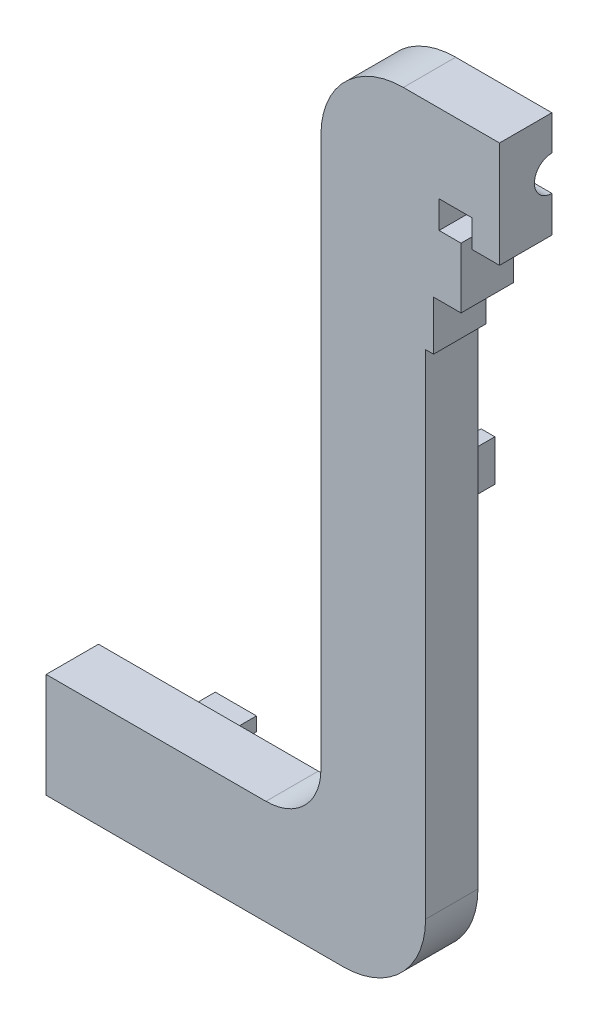
SolidWorks part; units mm, degrees
material "ABS"
ref_plane "Front Plane" through (0, 0, 0) normal (0, 0, 1) x (1, 0, 0)
ref_plane "Top Plane" through (0, 0, 0) normal (0, 1, 0) x (1, 0, 0)
ref_plane "Right Plane" through (0, 0, 0) normal (1, 0, 0) x (0, 0, -1)
sketch "Sketch1" plane through (0, 0, 0) normal (0, 0, 1) x (1, 0, 0)
  line L0 (-100, 0) -> (0, 0)
  line L1 (0, 0) -> (0, 250)
  line L2 (0, 250) -> (65, 250)
  line L3 (65, 250) -> (65, 211.9)
  line L4 (-100, -38.1) -> (38.1, -38.1)
  line L5 (38.1, -38.1) -> (38.1, 211.9)
  line L6 (38.1, 211.9) -> (65, 211.9)
  line L7 (-100, 0) -> (-100, -38.1)
  dimension "D1" = 100
  dimension "D2" = 250
  dimension "D3" = 65
  dimension "D4" = 38.1
extrude "Boss-Extrude1" add sketch "Sketch1" along normal blind 19.05
sketch "Sketch2" plane through (0, 0, 0) normal (0, 0, -1) x (-1, 0, 0)
  line L0 (-65, 230.95) -> (-39.05, 230.95)
  line L1 (-65, 211.9) -> (-65, 250) construction
  line L2 (100, -19.05) -> (0.95, -19.05)
  line L3 (100, 0) -> (100, -38.1) construction
  line L5 (-19.05, 210.95) -> (-19.05, 0.95)
  line L7 (-38.1, -38.1) -> (-38.1, 211.9) construction
  arc A0 (0.95, -19.05) -> (-19.05, 0.95) centre (0.95, 0.95) cw
  arc A1 (-39.05, 230.95) -> (-19.05, 210.95) centre (-39.05, 210.95) cw
  dimension "D2" = 20
  dimension "D1" = 19.05
sweep "Cut-Sweep1" cut path "Sketch2" circular profile diameter 12.7 parameters "D3"=12.7
fillet "Fillet1" radius 30 2 edges at (38.1, -38.1, 9.525) (0, 250, 9.525)
fillet "Fillet2" radius 20 1 edges at (0, 0, 9.525)
sketch "Sketch10" plane through (0, 0, 0) normal (0, 0, -1) x (-1, 0, 0)
  line L0 (0, 120) -> (-12.7, 120) construction
  line L17 (-19.05, 0.95) -> (-19.05, 210.95) construction
  line L18 (-12.7, 0.95) -> (-25.4, 0.95) construction
  line L23 (-12.7, 210.95) -> (-25.4, 210.95) construction
  line L24 (0, 220) -> (0, 20) construction
  line L29 (100, -19.05) -> (0.95, -19.05) construction
  line L30 (100, -25.4) -> (100, -12.7) construction
  line L35 (0.95, -12.7) -> (0.95, -25.4) construction
  line L36 (60, 0) -> (60, -12.7) construction
  line L47 (-3.85, 127.5) -> (-8.85, 127.5)
  line L48 (-3.85, 127.5) -> (-3.85, 112.5)
  line L49 (-3.85, 112.5) -> (-8.85, 112.5)
  line L50 (-8.85, 127.5) -> (-8.85, 112.5)
  line L51 (-3.85, 127.5) -> (-8.85, 112.5) construction
  line L52 (-3.85, 112.5) -> (-8.85, 127.5) construction
  line L53 (-12.7, 210.95) -> (-12.7, 0.95) construction
  line L54 (-34.25, 112.5) -> (-29.25, 127.5) construction
  line L55 (-34.25, 127.5) -> (-29.25, 112.5) construction
  line L56 (-38.1, 120) -> (-25.4, 120) construction
  line L57 (-29.25, 127.5) -> (-29.25, 112.5)
  line L58 (-34.25, 112.5) -> (-29.25, 112.5)
  line L59 (-34.25, 127.5) -> (-34.25, 112.5)
  line L60 (-34.25, 127.5) -> (-29.25, 127.5)
  line L61 (67.5, -3.85) -> (52.5, -3.85)
  line L62 (67.5, -3.85) -> (67.5, -8.85)
  line L63 (67.5, -8.85) -> (52.5, -8.85)
  line L64 (52.5, -3.85) -> (52.5, -8.85)
  line L65 (67.5, -3.85) -> (52.5, -8.85) construction
  line L66 (67.5, -8.85) -> (52.5, -3.85) construction
  line L67 (20, 0) -> (100, 0) construction
  line L68 (0.95, -12.7) -> (100, -12.7) construction
  line L69 (67.5, -29.25) -> (52.5, -34.25) construction
  line L70 (67.5, -34.25) -> (52.5, -29.25) construction
  line L71 (60, -38.1) -> (60, -25.4) construction
  line L72 (52.5, -34.25) -> (52.5, -29.25)
  line L73 (67.5, -29.25) -> (52.5, -29.25)
  line L74 (67.5, -34.25) -> (67.5, -29.25)
  line L75 (67.5, -34.25) -> (52.5, -34.25)
  point P16 (-6.35, 120)
  point P26 (60, -6.35)
  point P49 (-6.35, 120)
  point P56 (-31.75, 120)
  point P71 (60, -31.75)
  dimension "D4" = 5
  dimension "D5" = 15
  dimension "D6" = 15
  dimension "D7" = 5
extrude "Boss-Extrude2" add sketch "Sketch10" along normal blind 10
fillet "Fillet3" radius 1 16 edges at (-60, -29.25, 0) (-52.5, -6.35, 0) (-52.5, -31.75, 0) (-60, -34.25, 0) (-60, -8.85, 0) (-67.5, -31.75, 0) (-67.5, -6.35, 0) (-60, -3.85, 0) (6.35, 127.5, 0) (8.85, 120, 0) (3.85, 120, 0) (6.35, 112.5, 0) (31.75, 112.5, 0) (29.25, 120, 0) (31.75, 127.5, 0) (34.25, 120, 0)
sketch "Sketch13" plane through (0, 0, 19.05) normal (0, 0, 1) x (1, 0, 0)
  line L0 (38.1, 221.425) -> (38.1, 140.9734) construction
  line L1 (38.1, -8.1) -> (38.1, 211.9) construction
  line L2 (65, 230.95) -> (65, 211.9) construction
  line L3 (65, 221.425) -> (38.1, 221.425) construction
  line L4 (55, 221.425) -> (43, 221.425)
  line L5 (43, 221.425) -> (43, 211.425)
  line L6 (55, 221.425) -> (55, 211.425)
  line L7 (43, 211.425) -> (51, 211.425)
  line L8 (51, 211.425) -> (51, 189.425)
  line L9 (55, 211.425) -> (65, 211.425)
  line L11 (51, 189.425) -> (41, 189.425)
  line L12 (41, 189.425) -> (41, 171.425)
  line L13 (41, 171.425) -> (36.5499, 171.425)
  line L14 (36.5499, 171.425) -> (36.5499, 223.573)
  line L15 (36.5499, 223.573) -> (65, 223.573)
  line L16 (65, 223.573) -> (65, 211.9)
  line L18 (65, 211.9) -> (65, 211.425)
  dimension "D1" = 10
  dimension "D2" = 12
  dimension "D3" = 10
  dimension "D4" = 10
  dimension "D5" = 8
  dimension "D6" = 22
  dimension "D7" = 10
  dimension "D8" = 18
  dimension "D9" = 52.148
extrude "Boss-Extrude3" add sketch "Sketch13" against normal blind 19.05
sketch "Sketch14" plane through (0, 0, 19.05) normal (0, 0, 1) x (1, 0, 0)
  line L0 (65, 211.425) -> (65, 250) construction
  line L1 (55, 221.42) -> (43, 221.42)
  line L2 (55, 221.42) -> (55, 211.42)
  line L3 (55, 211.42) -> (43, 211.42)
  line L4 (43, 221.42) -> (43, 211.42)
  line L5 (55, 221.42) -> (43, 211.42) construction
  line L6 (55, 211.42) -> (43, 221.42) construction
  line L7 (65, 230.95) -> (39.05, 230.95) construction
  point P0 (49, 216.42)
  dimension "D1" = 10
  dimension "D2" = 12
  dimension "D3" = 10
  dimension "D4" = 9.53
extrude "Cut-Extrude1" cut sketch "Sketch14" against normal blind 39
